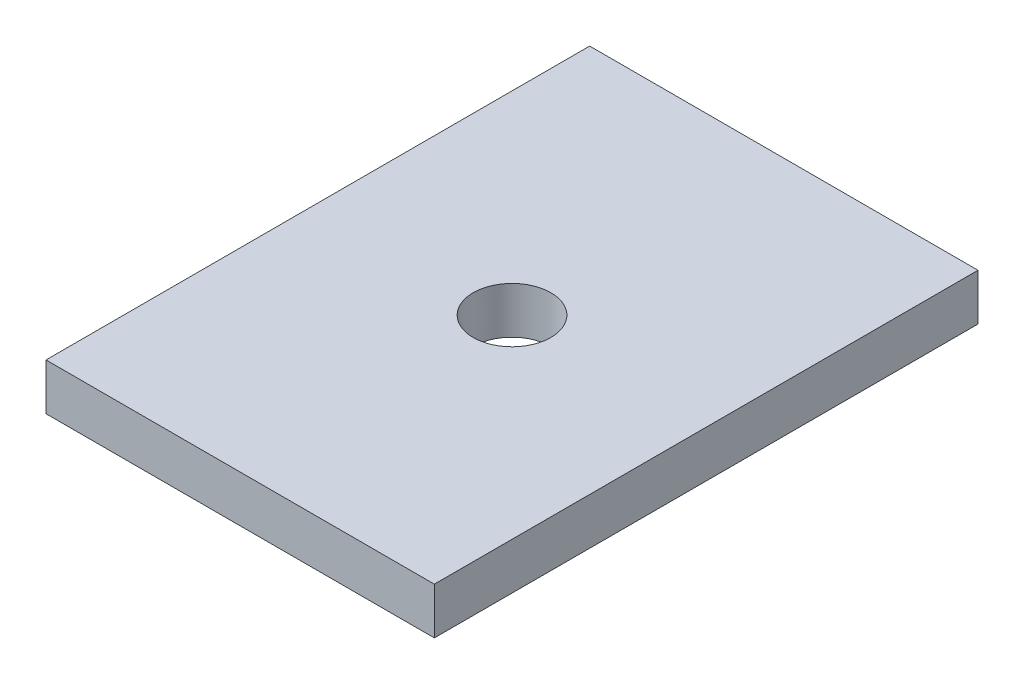
SolidWorks part; units mm, degrees
ref_plane "Front Plane" through (0, 0, 0) normal (0, 0, 1) x (1, 0, 0)
ref_plane "Top Plane" through (0, 0, 0) normal (0, 1, 0) x (1, 0, 0)
ref_plane "Right Plane" through (0, 0, 0) normal (1, 0, 0) x (0, 0, -1)
sketch "Sketch1" plane through (0, 0, 0) normal (0, 1, 0) x (1, 0, 0)
  line L1 (0, 0) -> (25, 0)
  line L2 (0, 0) -> (0, 35)
  line L3 (0, 35) -> (25, 35)
  line L4 (25, 0) -> (25, 35)
  dimension "D1" = 35
  dimension "D2" = 25
extrude "Boss-Extrude1" add sketch "Sketch1" along normal blind 3
sketch "Sketch2" plane through (0, 0, 0) normal (0, 1, 0) x (1, 0, 0)
  line L0 (0, 35) -> (25, 0) construction
  line L1 (25, 0) -> (25, 35) construction
  line L2 (25, 35) -> (0, 0) construction
  circle A0 centre (12.5, 17.5) radius 2.5
  dimension "D1" = 5
extrude "Cut-Extrude1" cut sketch "Sketch2" along normal blind 12
